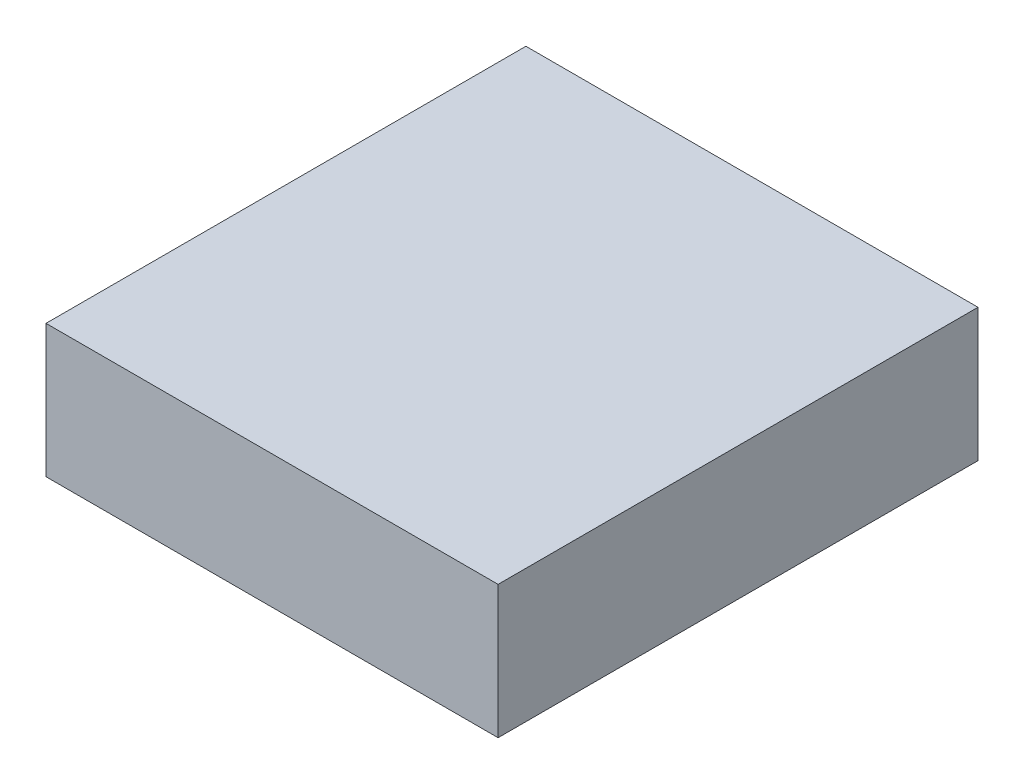
SolidWorks part; units mm, degrees
ref_plane "Front Plane" through (0, 0, 0) normal (0, 0, 1) x (1, 0, 0)
ref_plane "Top Plane" through (0, 0, 0) normal (0, 1, 0) x (1, 0, 0)
ref_plane "Right Plane" through (0, 0, 0) normal (1, 0, 0) x (0, 0, -1)
sketch "Sketch1" plane through (0, 0, 0) normal (0, 0, 1) x (1, 0, 0)
  line L1 (-32.5, -9.55) -> (32.5, -9.55)
  line L2 (-32.5, -9.55) -> (-32.5, 9.55)
  line L3 (-32.5, 9.55) -> (32.5, 9.55)
  line L4 (32.5, -9.55) -> (32.5, 9.55)
  line L5 (-32.5, -9.55) -> (32.5, 9.55) construction
  line L6 (-32.5, 9.55) -> (32.5, -9.55) construction
  point P0 (0, 0)
  dimension "D1" = 19.1
  dimension "D2" = 65
extrude "Boss-Extrude1" add sketch "Sketch1" along normal blind 69
